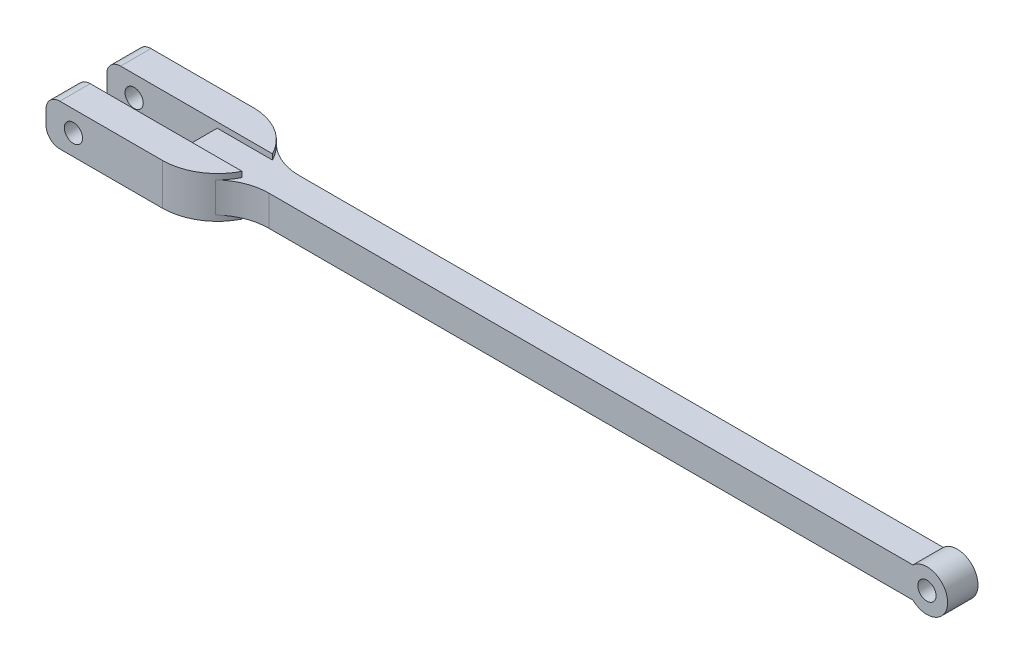
SolidWorks part; units mm, degrees
material "6061 Alloy"
ref_plane "Front Plane" through (0, 0, 0) normal (0, 0, 1) x (1, 0, 0)
ref_plane "Top Plane" through (0, 0, 0) normal (0, 1, 0) x (1, 0, 0)
ref_plane "Right Plane" through (0, 0, 0) normal (1, 0, 0) x (0, 0, -1)
sketch "Sketch1" plane through (0, 0, 0) normal (1, 0, 0) x (0, 0, -1)
  line L1 (6.985, -7.0062) -> (-6.985, -7.0062)
  line L2 (6.985, -7.0062) -> (6.985, 7.0062)
  line L3 (6.985, 7.0062) -> (-6.985, 7.0062)
  line L4 (-6.985, -7.0062) -> (-6.985, 7.0062)
  line L5 (6.985, -7.0062) -> (-6.985, 7.0062) construction
  line L6 (6.985, 7.0062) -> (-6.985, -7.0062) construction
  point P0 (0, 0)
  dimension "D1" = 13.97
extrude "Boss-Extrude1" add sketch "Sketch1" along normal blind 213.36 and the other way blind 127
sketch "Sketch2" plane through (0, 0, 0) normal (0, 0, 1) x (1, 0, 0)
  line L0 (213.36, 7.0062) -> (213.36, -7.0062) construction
  circle A0 centre (213.36, 0) radius 9.525
  dimension "D1" = 19.05
extrude "Boss-Extrude2" add sketch "Sketch2" along normal up to surface and the other way up to surface up to face at (43.18, 0, 6.985) other way up to face at (43.18, 0, -6.985)
sketch "Sketch3" plane through (0, 0, 0) normal (0, 0, 1) x (1, 0, 0)
  circle A0 centre (213.36, 0) radius 4.191
  dimension "D1" = 8.382
extrude "Cut-Extrude1" cut sketch "Sketch3" against normal through all and the other way through all
sketch "Sketch6" plane through (0, 0, 0) normal (0, 1, 0) x (1, 0, 0)
  line L0 (-127, 6.985) -> (-177.8, 6.985)
  line L1 (-177.8, 6.985) -> (-177.8, 20.955)
  line L2 (-177.8, 20.955) -> (-124.2854, 20.955)
  line L3 (-127, 6.985) -> (206.9071, 6.985) construction
  line L4 (-127, 6.985) -> (-101.6, 6.985)
  arc A0 (-124.2854, 20.955) -> (-101.6, 6.985) centre (-124.2854, -4.449) cw
  dimension "D2" = 25.4
  dimension "D1" = 13.97
  dimension "D3" = 13.97
  dimension "D4" = 50.8
extrude "Boss-Extrude3" add sketch "Sketch6" against normal blind 9.525 and the other way blind 9.525
fillet "Fillet1" radius 25.4 1 edges at (-101.6, 0, -6.985)
mirror "Mirror3" about plane through (0, 0, 0) normal (0, 0, 1) of "Boss-Extrude3"
fillet "Fillet2" radius 25.4 1 edges at (-101.6, 0, 6.985)
fillet "Fillet5" radius 6.35 4 edges at (-177.8, -9.525, 13.97) (-177.8, -9.525, -13.97) (-177.8, 9.525, -13.97) (-177.8, 9.525, 13.97)
sketch "Sketch8" plane through (0, 0, 0) normal (0, 0, 1) x (1, 0, 0)
sketch "Sketch10" plane through (0, 0, 0) normal (0, 0, 1) x (1, 0, 0)
  line L0 (23.0505, 0) -> (-23.0505, 0) construction
  circle A0 centre (-165.1984, 0) radius 4.191
  dimension "D1" = 8.382
extrude "Cut-Extrude4" cut sketch "Sketch10" against normal through all and the other way through all
